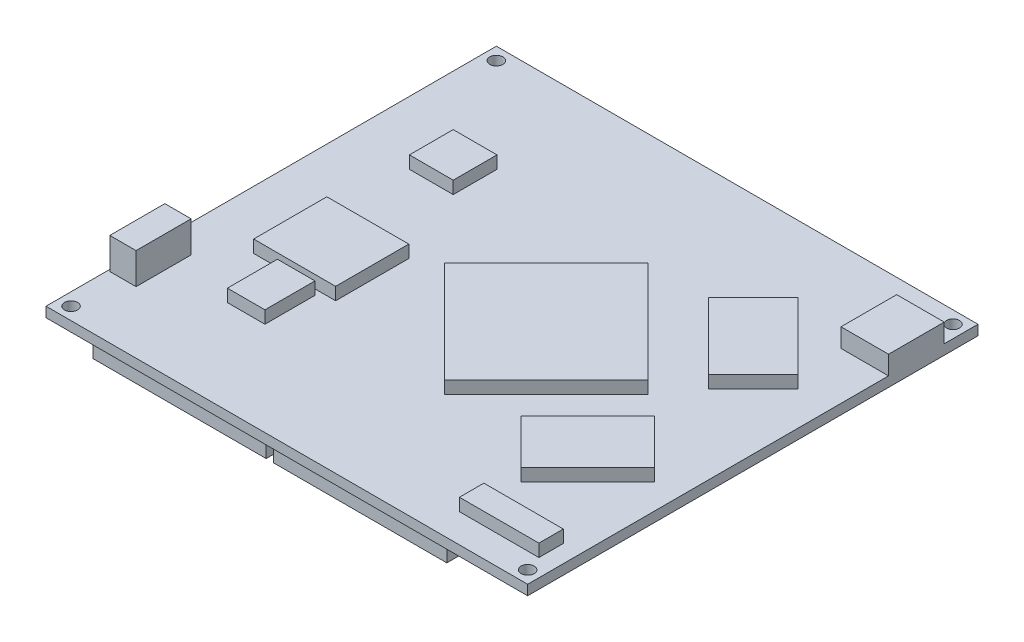
SolidWorks part; units mm, degrees
ref_plane "前视基准面" through (0, 0, 0) normal (0, 0, 1) x (1, 0, 0)
ref_plane "上视基准面" through (0, 0, 0) normal (0, 1, 0) x (1, 0, 0)
ref_plane "右视基准面" through (0, 0, 0) normal (1, 0, 0) x (0, 0, -1)
sketch "草图1" plane through (0, 0, 0) normal (0, 1, 0) x (1, 0, 0)
  line L1 (0, 0) -> (77, 0)
  line L2 (0, 0) -> (0, -72)
  line L3 (0, -72) -> (77, -72)
  line L4 (77, 0) -> (77, -72)
  line L5 (2, -2) -> (75, -2) construction
  line L6 (2, -2) -> (2, -70) construction
  line L7 (2, -70) -> (75, -70) construction
  line L8 (75, -2) -> (75, -70) construction
  circle A0 centre (2, -2) radius 1.05
  circle A1 centre (2, -70) radius 1.05
  circle A2 centre (75, -2) radius 1.05
  circle A3 centre (75, -70) radius 1.05
  dimension "D7" = 2.1
  dimension "D8" = 2.1
  dimension "D9" = 2.1
  dimension "D10" = 2.1
  dimension "D1" = 77
  dimension "D2" = 72
  dimension "D3" = 2
  dimension "D4" = 2
  dimension "D5" = 2
  dimension "D6" = 2
extrude "凸台-拉伸1" add sketch "草图1" along normal blind 1.6
sketch "草图2" plane through (0, 1.6, 0) normal (0, 1, 0) x (1, 0, 0)
  line L0 (0, -72) -> (77, -72) construction
  line L1 (10.1, -17) -> (17.1, -17)
  line L2 (10.1, -17) -> (10.1, -24)
  line L3 (10.1, -24) -> (17.1, -24)
  line L4 (17.1, -17) -> (17.1, -24)
  line L5 (0, 0) -> (0, -72) construction
  line L6 (44.1, -19.8731) -> (27.8365, -36.1365)
  line L7 (9.3, -36.4) -> (22.4, -36.4)
  line L8 (9.3, -36.4) -> (9.3, -48.1)
  line L9 (9.3, -48.1) -> (22.4, -48.1)
  line L10 (22.4, -36.4) -> (22.4, -48.1)
  line L11 (20, -49) -> (14, -49)
  line L12 (20, -49) -> (20, -57)
  line L13 (20, -57) -> (14, -57)
  line L14 (14, -49) -> (14, -57)
  line L15 (27.8365, -19.8731) -> (60.3635, -19.8731) construction
  line L16 (27.8365, -19.8731) -> (27.8365, -52.4) construction
  line L17 (27.8365, -52.4) -> (60.3635, -52.4) construction
  line L18 (60.3635, -19.8731) -> (60.3635, -52.4) construction
  line L19 (27.8365, -36.1365) -> (44.1, -52.4)
  line L20 (44.1, -52.4) -> (60.3635, -36.1365)
  line L21 (60.3635, -36.1365) -> (44.1, -19.8731)
  line L22 (65.8355, -40.5809) -> (55.1582, -51.2582)
  line L23 (55.1582, -40.5809) -> (72.9773, -40.5809) construction
  line L24 (55.1582, -40.5809) -> (55.1582, -58.4) construction
  line L25 (55.1582, -58.4) -> (72.9773, -58.4) construction
  line L26 (72.9773, -40.5809) -> (72.9773, -58.4) construction
  line L31 (55.1582, -51.2582) -> (62.3, -58.4)
  line L32 (62.3, -58.4) -> (72.9773, -47.7227)
  line L33 (72.9773, -47.7227) -> (65.8355, -40.5809)
  line L34 (60.8645, -12.6809) -> (53.7227, -19.8227)
  line L35 (53.7227, -12.6809) -> (71.5418, -12.6809) construction
  line L36 (53.7227, -12.6809) -> (53.7227, -30.5) construction
  line L37 (53.7227, -30.5) -> (71.5418, -30.5) construction
  line L38 (71.5418, -12.6809) -> (71.5418, -30.5) construction
  line L39 (53.7227, -19.8227) -> (64.4, -30.5)
  line L40 (64.4, -30.5) -> (71.5418, -23.3582)
  line L41 (71.5418, -23.3582) -> (60.8645, -12.6809)
  line L42 (77, -72) -> (77, 0) construction
  line L43 (74.2, -67.4) -> (61.5, -67.4)
  line L44 (74.2, -67.4) -> (74.2, -63.5)
  line L45 (74.2, -63.5) -> (61.5, -63.5)
  line L46 (61.5, -67.4) -> (61.5, -63.5)
  dimension "D1" = 48
  dimension "D2" = 7
  dimension "D3" = 10.1
  dimension "D4" = 7
  dimension "D5" = 9.3
  dimension "D6" = 13.1
  dimension "D7" = 23.9
  dimension "D8" = 11.7
  dimension "D9" = 14
  dimension "D10" = 15
  dimension "D11" = 6
  dimension "D12" = 8
  dimension "D13" = 44.1
  dimension "D14" = 19.6
  dimension "D15" = 45
  dimension "D16" = 23
  dimension "D17" = 62.3
  dimension "D18" = 13.6
  dimension "D19" = 45
  dimension "D20" = 45
  dimension "D21" = 15.1
  dimension "D22" = 10.1
  dimension "D23" = 64.4
  dimension "D24" = 41.5
  dimension "D25" = 45
  dimension "D26" = 45
  dimension "D27" = 15.1
  dimension "D28" = 10.1
  dimension "D29" = 2.8
  dimension "D30" = 4.6
  dimension "D31" = 12.7
  dimension "D32" = 3.9
extrude "凸台-拉伸2" add sketch "草图2" along normal blind 2
sketch "草图3" plane through (0, 1.6, 0) normal (0, 1, 0) x (1, 0, 0)
  line L0 (77, -72) -> (77, 0) construction
  line L1 (77, -5.4) -> (69.4, -5.4)
  line L2 (77, -5.4) -> (77, -14.3)
  line L3 (77, -14.3) -> (69.4, -14.3)
  line L4 (69.4, -5.4) -> (69.4, -14.3)
  line L5 (77, 0) -> (0, 0) construction
  dimension "D1" = 7.6
  dimension "D2" = 5.4
  dimension "D3" = 8.9
extrude "凸台-拉伸3" add sketch "草图3" along normal blind 3
sketch "草图5" plane through (0, 1.6, 0) normal (0, 1, 0) x (1, 0, 0)
  line L0 (0, 0) -> (0, -72) construction
  line L1 (0.3, -62.1) -> (4.5, -62.1)
  line L2 (0.3, -62.1) -> (0.3, -53.3)
  line L3 (0.3, -53.3) -> (4.5, -53.3)
  line L4 (4.5, -62.1) -> (4.5, -53.3)
  line L5 (0, -72) -> (77, -72) construction
  dimension "D1" = 0.3
  dimension "D2" = 9.9
  dimension "D3" = 4.2
  dimension "D4" = 8.8
extrude "凸台-拉伸4" add sketch "草图5" along normal blind 5
sketch "草图6" plane through (0, 0, 0) normal (0, -1, 0) x (1, 0, 0)
  line L0 (0, 0) -> (0, 72) construction
  line L1 (4.4, 68.9) -> (32.1, 68.9)
  line L2 (4.4, 68.9) -> (4.4, 65)
  line L3 (4.4, 65) -> (32.1, 65)
  line L4 (32.1, 68.9) -> (32.1, 65)
  line L5 (0, 72) -> (77, 72) construction
  line L6 (77, 0) -> (0, 0) construction
  line L7 (33.28, 68.9) -> (60.98, 68.9)
  line L8 (33.28, 68.9) -> (33.28, 65)
  line L9 (33.28, 65) -> (60.98, 65)
  line L10 (60.98, 68.9) -> (60.98, 65)
  line L11 (4.4, 3.1) -> (32.1, 3.1)
  line L12 (4.4, 3.1) -> (4.4, 7)
  line L13 (4.4, 7) -> (32.1, 7)
  line L14 (32.1, 3.1) -> (32.1, 7)
  line L16 (33.28, 7) -> (60.98, 7)
  line L17 (33.28, 7) -> (33.28, 3.1)
  line L18 (33.28, 3.1) -> (60.98, 3.1)
  line L19 (60.98, 7) -> (60.98, 3.1)
  dimension "D1" = 4.4
  dimension "D2" = 3.1
  dimension "D3" = 27.7
  dimension "D4" = 3.9
  dimension "D5" = 1.18
  dimension "D6" = 27.7
  dimension "D7" = 3.1
  dimension "D8" = 3.9
extrude "凸台-拉伸5" add sketch "草图6" along normal blind 5
